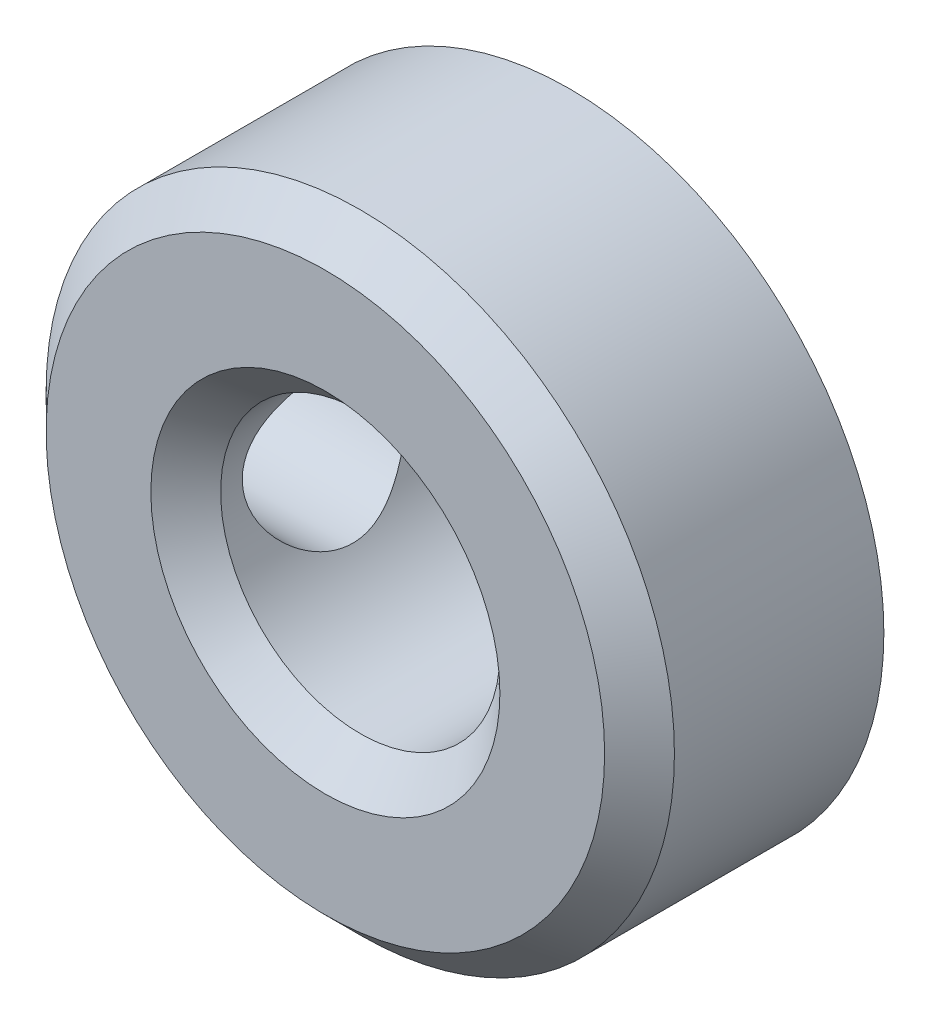
SolidWorks part; units mm, degrees
ref_plane "Alzado" through (0, 0, 0) normal (0, 0, 1) x (1, 0, 0)
ref_plane "Planta" through (0, 0, 0) normal (0, 1, 0) x (1, 0, 0)
ref_plane "Vista lateral" through (0, 0, 0) normal (1, 0, 0) x (0, 0, -1)
sketch "Croquis1" plane through (0, 0, 0) normal (0, 0, 1) x (1, 0, 0)
  circle A0 centre (0, 0) radius 9
  dimension "D1" = 18
extrude "Saliente-Extruir1" add sketch "Croquis1" along normal blind 8
sketch "Croquis2" plane through (0, 0, 8) normal (0, 0, 1) x (1, 0, 0)
  circle A0 centre (0, 0) radius 4
  dimension "D1" = 8
extrude "Cortar-Extruir1" cut sketch "Croquis2" against normal through all
chamfer "Chaflán1" distance 1 angle 45 2 edges at (4, 0, 8) (9, 0, 8)
sketch "Croquis3" plane through (0, 0, 0) normal (1, 0, 0) x (0, 0, -1)
  line L0 (0, 0) -> (-8, 0) construction
  line L1 (-8, 8) -> (-8, -8) construction
  circle A0 centre (-4, 0) radius 2.3813
  dimension "D1" = 4.7625
extrude "Cortar-Extruir2" cut sketch "Croquis3" against normal blind 10
sketch "Croquis4" plane through (0, 0, 0) normal (0, 0, -1) x (-1, 0, 0)
  circle A0 centre (0, 0) radius 5.5
  circle A1 centre (0, 0) radius 11.3905
  dimension "D1" = 11
extrude "Cortar-Extruir3" cut sketch "Croquis4" against normal blind 1
